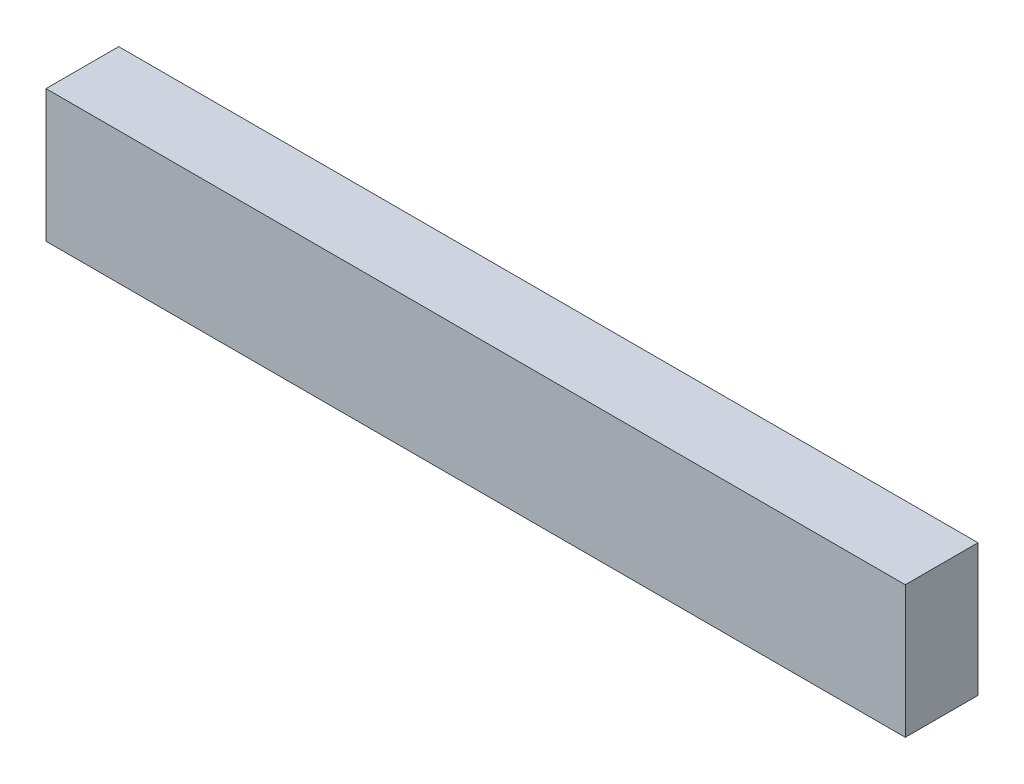
SolidWorks part; units mm, degrees
ref_plane "Front Plane" through (0, 0, 0) normal (0, 0, 1) x (1, 0, 0)
ref_plane "Top Plane" through (0, 0, 0) normal (0, 1, 0) x (1, 0, 0)
ref_plane "Right Plane" through (0, 0, 0) normal (1, 0, 0) x (0, 0, -1)
sketch "Sketch1" plane through (0, 0, 0) normal (1, 0, 0) x (0, 0, -1)
  line L1 (0, 0) -> (279.4, 0)
  line L2 (0, 0) -> (0, 508)
  line L3 (0, 508) -> (279.4, 508)
  line L4 (279.4, 0) -> (279.4, 508)
  dimension "D1" = 279.4
  dimension "D2" = 508
extrude "Boss-Extrude1" add sketch "Sketch1" along normal blind 3302
